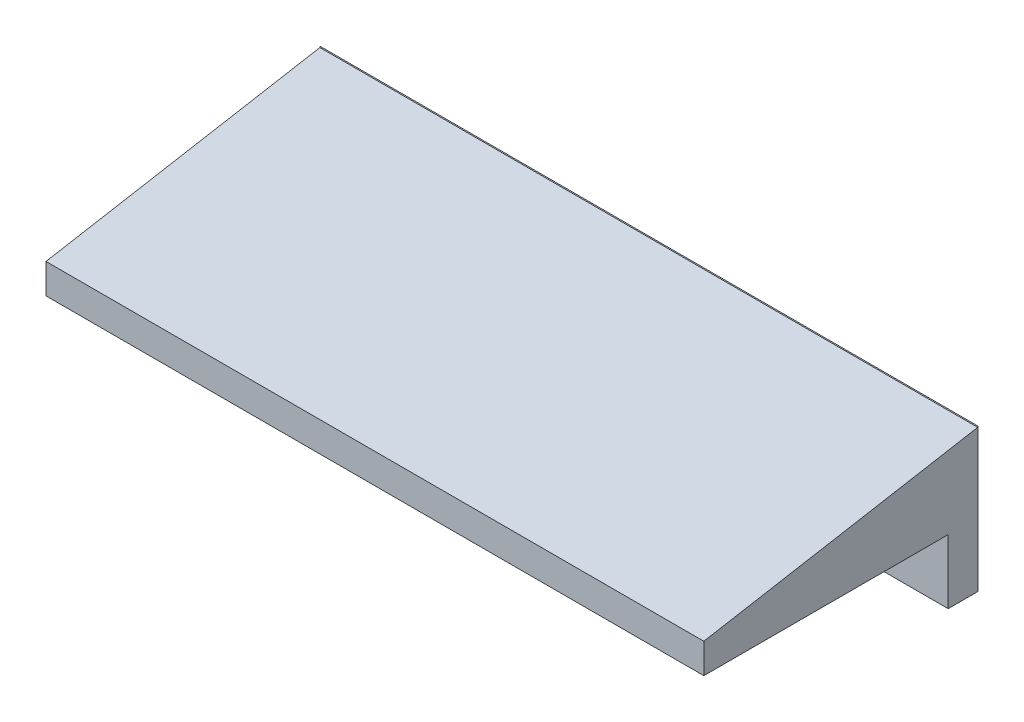
SolidWorks part; units mm, degrees
ref_plane "Front" through (0, 0, 0) normal (0, 0, 1) x (1, 0, 0)
ref_plane "Top" through (0, 0, 0) normal (0, 1, 0) x (1, 0, 0)
ref_plane "Right" through (0, 0, 0) normal (1, 0, 0) x (0, 0, -1)
sketch "Sketch1" plane through (0, 0, 0) normal (0, 1, 0) x (1, 0, 0)
  line L1 (-35, -13) -> (35, -13)
  line L2 (-35, -13) -> (-35, 13)
  line L3 (-35, 13) -> (35, 13)
  line L4 (35, -13) -> (35, 13)
  line L5 (-35, -13) -> (35, 13) construction
  line L6 (-35, 13) -> (35, -13) construction
  point P0 (0, 0)
  dimension "D1" = 26
  dimension "D2" = 70
extrude "Boss-Extrude1" add sketch "Sketch1" along normal blind 3.175
sketch "Sketch2" plane through (0, 0, -13) normal (0, 0, -1) x (-1, 0, 0)
  line L0 (35, 3.175) -> (-35, 3.175)
  line L1 (35, 3.175) -> (35, -6.825)
  line L2 (-35, 3.175) -> (-35, -6.825)
  line L3 (35, -6.825) -> (-35, -6.825)
  dimension "D1" = 10
  dimension "D2" = 70
extrude "Boss-Extrude2" add sketch "Sketch2" along normal blind 3.175
sketch "Sketch3" plane through (0, 0, -13) normal (0, 0, 1) x (1, 0, 0)
  line L0 (28.575, -3.825) -> (-14.914, -3.825)
  line L3 (-14.914, -3.825) -> (-28.575, -3.825)
  line L4 (35, -6.825) -> (-35, -6.825) construction
  circle A1 centre (-14.914, -3.825) radius 1.6
  circle A2 centre (28.575, -3.825) radius 1.6
  circle A3 centre (-28.575, -3.825) radius 1.6
  dimension "D3" = 13.661
  dimension "D1" = 3
extrude "Cut-Extrude1" cut sketch "Sketch3" against normal blind 3.175
sketch "Sketch4" plane through (35, 0, 0) normal (1, 0, 0) x (0, 0, -1)
  line L0 (-13, 3.175) -> (16.1432, 8.3137)
  line L1 (-13, 3.175) -> (16.175, 3.175) construction
  line L2 (16.175, 3.175) -> (16.175, 8.4128)
  line L3 (16.175, 3.175) -> (-13, 3.175)
  line L4 (16.175, 8.4128) -> (16.1432, 8.3137)
  line L9 (-13, 0) -> (13, 0)
  line L10 (13, 0) -> (13, -6.825)
  line L11 (13, -6.825) -> (16.175, -6.825)
  line L12 (13, -6.825) -> (16.175, -6.825)
  line L13 (16.175, 3.175) -> (-13, 3.175)
  line L14 (-13, 3.175) -> (-13, 0)
  line L15 (-13, 0) -> (13, 0)
  line L16 (13, 0) -> (13, -6.825)
  line L20 (-13, 3.175) -> (-13, 0)
  line L22 (16.175, -6.825) -> (16.175, 3.175)
  line L23 (16.175, -6.825) -> (16.175, 3.175)
  line M6 (16.175, 3.175) -> (-13, 3.175)
  dimension "D1" = 10
  dimension "D2" = 0
extrude "Boss-Extrude3" add sketch "Sketch4" against normal blind 70 contours L2 L4 L0 M6
sketch "Sketch5" plane through (0, 0, -16.175) normal (0, 0, -1) x (-1, 0, 0)
  line L0 (-35, -6.825) -> (35, -6.825) construction
  line L1 (-25, -6.825) -> (3, -6.825)
  line L2 (-25, -6.825) -> (-25, 0)
  line L3 (-25, 0) -> (3, 0)
  line L4 (3, -6.825) -> (3, 0)
  line L5 (35, -6.825) -> (35, 8.4128) construction
  line L6 (-35, 8.4128) -> (-35, -6.825) construction
  dimension "D1" = 32
  dimension "D2" = 10
  dimension "D3" = 6.825
extrude "Cut-Extrude2" cut sketch "Sketch5" against normal blind 10
